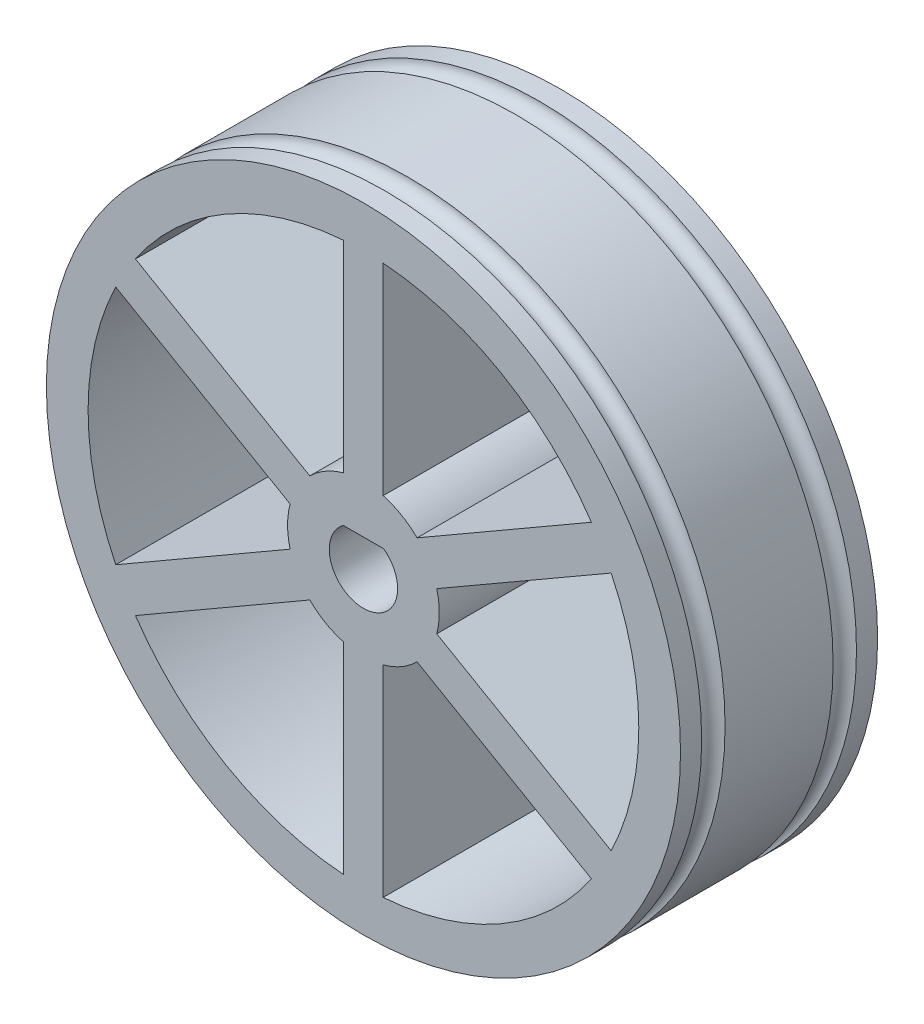
SolidWorks part; units mm, degrees
ref_plane "Front Plane" through (0, 0, 0) normal (0, 0, 1) x (1, 0, 0)
ref_plane "Top Plane" through (0, 0, 0) normal (0, 1, 0) x (1, 0, 0)
ref_plane "Right Plane" through (0, 0, 0) normal (1, 0, 0) x (0, 0, -1)
sketch "Sketch1" plane through (0, 0, 0) normal (0, 0, 1) x (1, 0, 0)
  circle A0 centre (0, 0) radius 24.13
  circle A1 centre (0, 0) radius 20.955
  circle A2 centre (0, 0) radius 2.6
  circle A3 centre (0, 0) radius 5.775
  dimension "D1" = 48.26
  dimension "D2" = 3.175
  dimension "D3" = 5.2
  dimension "D4" = 3.175
extrude "Boss-Extrude1" add sketch "Sketch1" along normal blind 15 contours A0 A1 | A3 A2
sketch "Sketch3" plane through (0, 0, 0) normal (0, 0, -1) x (-1, 0, 0)
  line L0 (0, 0) -> (0, 2.6) construction
  line L1 (1.5, 2.6) -> (-1.5, 2.6)
  line L2 (0, 2.6) -> (0, 20.955) construction
  line L3 (1.5, 20.955) -> (-1.5, 20.955)
  line L4 (-1.5, 20.955) -> (-1.5, 2.6)
  line L5 (1.5, 20.955) -> (1.5, 2.6)
  circle A0 centre (0, 0) radius 2.6 construction
  circle A1 centre (0, 0) radius 20.955 construction
  point P7 (0, 2.6)
  point P14 (0, 20.955)
  dimension "D1" = 3
  dimension "D2" = 3
extrude "Boss-Extrude3" add sketch "Sketch3" against normal up to surface (15 mm away) up to face at (2.6, 0, 15)
pattern_circular "CirPattern1" count 6 over 360 about axis through (0, 0, 0) along (0, 0, 1) of "Boss-Extrude3"
sketch "Sketch4" plane through (0, 0, 0) normal (1, 0, 0) x (0, 0, -1)
  line L0 (0, 0) -> (0, 24.13) construction
  line L1 (0, 24.13) -> (-15, 24.13) construction
  line L2 (-2.5, 24.13) -> (-12.5, 24.13) construction
  line L3 (0, 0) -> (-22.4846, 0) construction
  circle A0 centre (-12.5, 24.13) radius 0.89
  circle A1 centre (-2.5, 24.13) radius 0.89
  point P9 (-7.5, 24.13)
  dimension "D3" = 1.78
  dimension "D1" = 15
  dimension "D2" = 10
  dimension "D4" = 24.13
  dimension "D5" = 2.5
revolve "Cut-Revolve1" cut sketch "Sketch4" angle 360 about L3
sketch "Sketch5" plane through (0, 0, 15) normal (0, 0, 1) x (1, 0, 0)
  line L0 (0, 0) -> (0, 2.6) construction
  line L1 (-2.5, 2.6) -> (2.5, 2.6)
  line L2 (-2.5, 2.6) -> (-2.5, 2.1)
  line L3 (2.5, 2.6) -> (2.5, 2.1)
  line L4 (2.5, 2.1) -> (-2.5, 2.1)
  circle A0 centre (0, 0) radius 2.6 construction
  point P9 (0, 2.6)
  dimension "D1" = 5
  dimension "D2" = 0.5
extrude "Boss-Extrude4" add sketch "Sketch5" against normal up to surface (15 mm away) up to face at (6.3951, 11.0766, 0)
ref_plane "Plane2" through (0, 0, 12.5) normal (0, 0, 1) x (1, 0, 0)
ref_plane "Plane3" through (0, 0, 2.5) normal (0, 0, -1) x (-1, 0, 0)
